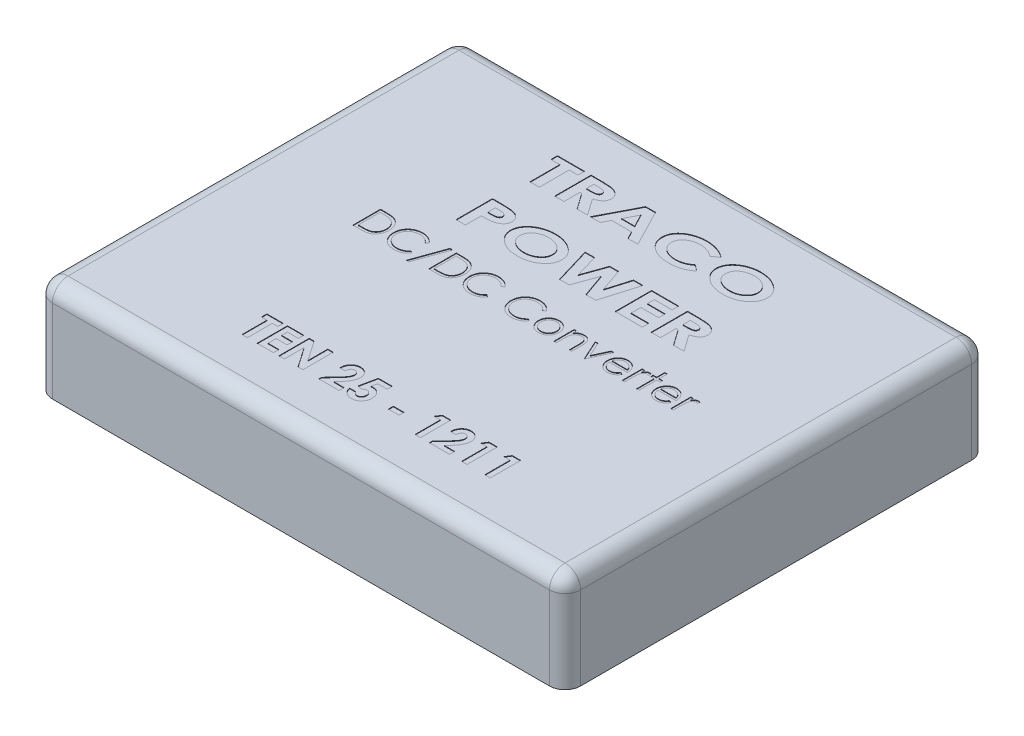
SolidWorks part; units mm, degrees
ref_plane "Plan de face" through (0, 0, 0) normal (0, 0, 1) x (1, 0, 0)
ref_plane "Plan de dessus" through (0, 0, 0) normal (0, 1, 0) x (1, 0, 0)
ref_plane "Plan de droite" through (0, 0, 0) normal (1, 0, 0) x (0, 0, -1)
sketch "Esquisse1" plane through (0, 0, 0) normal (0, 1, 0) x (1, 0, 0)
  line L1 (0, 0) -> (50.8, 0)
  line L2 (0, 0) -> (0, 40.6)
  line L3 (0, 40.6) -> (50.8, 40.6)
  line L4 (50.8, 0) -> (50.8, 40.6)
  dimension "D1" = 50.8
  dimension "D2" = 40.6
extrude "Boss.-Extru.1" add sketch "Esquisse1" along normal blind 9.5
fillet "Congé1" radius 1.5 8 edges at (0, 4.75, -40.6) (50.8, 4.75, -40.6) (50.8, 4.75, 0) (50.8, 9.5, -20.3) (25.4, 9.5, -40.6) (25.4, 9.5, 0) (0, 9.5, -20.3) (0, 4.75, 0)
sketch "Esquisse3" plane through (0, 9.5, 0) normal (0, 1, 0) x (1, 0, 0)
  text T0 "<b>TRACO</b>\r\n<b>POWER</b>" font "Century Gothic" height 3.5
extrude "Enlèv. mat.-Extru.1" cut sketch "Esquisse3" against normal blind 0.05
sketch "Esquisse5" plane through (0, 9.5, 0) normal (0, 1, 0) x (1, 0, 0)
  text T0 "<b>TEN 25 - 1211</b>" font "Century Gothic" height in points 11
extrude "Enlèv. mat.-Extru.2" cut sketch "Esquisse5" against normal blind 0.05
sketch "Esquisse6" plane through (0, 9.5, 0) normal (0, 1, 0) x (1, 0, 0)
  text T0 "DC/DC Converter" font "Century Gothic" height in points 10
extrude "Enlèv. mat.-Extru.3" cut sketch "Esquisse6" against normal blind 0.05
